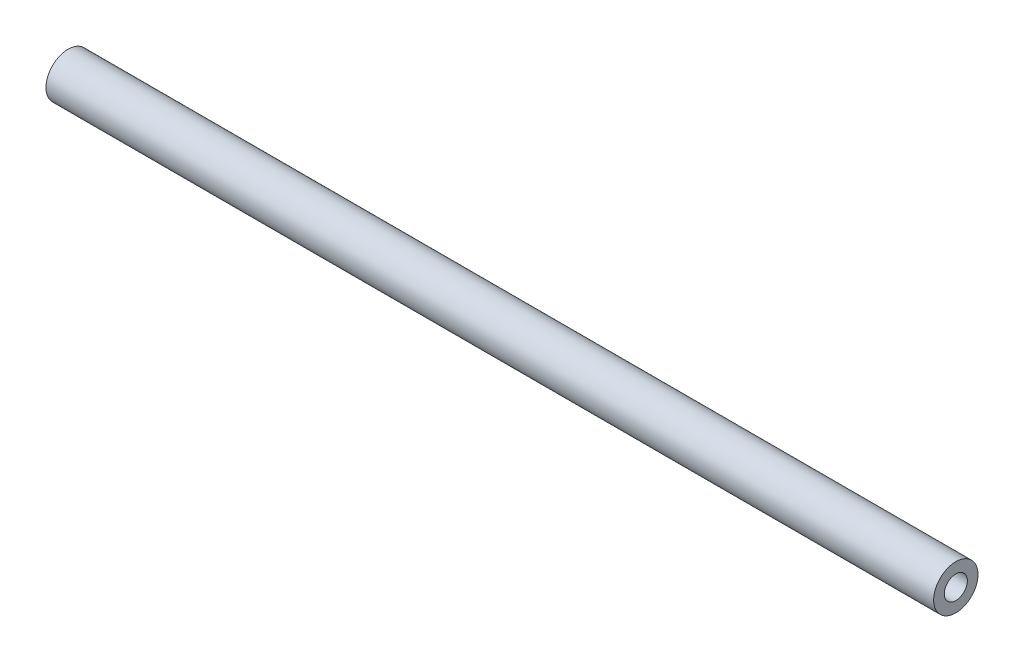
SolidWorks part; units mm, degrees
ref_plane "Front" through (0, 0, 0) normal (0, 0, 1) x (1, 0, 0)
ref_plane "Top" through (0, 0, 0) normal (0, 1, 0) x (1, 0, 0)
ref_plane "Right" through (0, 0, 0) normal (1, 0, 0) x (0, 0, -1)
sketch "Sketch1" plane through (0, 0, 0) normal (1, 0, 0) x (0, 0, -1)
  line L0 (3.302, 0) -> (6.35, 0) construction
  line L1 (3.302, 0) -> (6.35, 0) construction
  line L2 (4.826, 0) -> (4.826, 1.0672) construction
  circle A0 centre (0, 0) radius 6.35
  circle A1 centre (0, 0) radius 3.302
  point P4 (6.35, 0)
  point P5 (3.302, 0)
  dimension "OD" = 12.7
  dimension "ID" = 6.604
  dimension "Wall Thickness" = 3.048
sketch "Sketch2" plane through (0, 0, 0) normal (0, 0, 1) x (1, 0, 0)
  line L0 (-127, 0) -> (127, 0) construction
  point P2 (-111.125, 0)
  point P3 (111.125, 0)
  dimension "D1" = 15.875
  dimension "D2" = 15.875
sketch "Sketch3" plane through (0, 0, 0) normal (1, 0, 0) x (0, 0, -1)
  circle A0 centre (0, 0) radius 3.302 construction
  circle A1 centre (0, 0) radius 6.35 construction
  circle A2 centre (0, 0) radius 3.302
  circle A3 centre (0, 0) radius 6.35
extrude "Boss-Extrude1" add sketch "Sketch3" along normal mid plane 254
equation "\"D1@Boss-Extrude1\"=\"Length@Sketch2\""
equation "\"D1@Sketch2\"=\"OD@Sketch1\"*1.25"
equation "\"D2@Sketch2\"=\"D1@Sketch2\""
